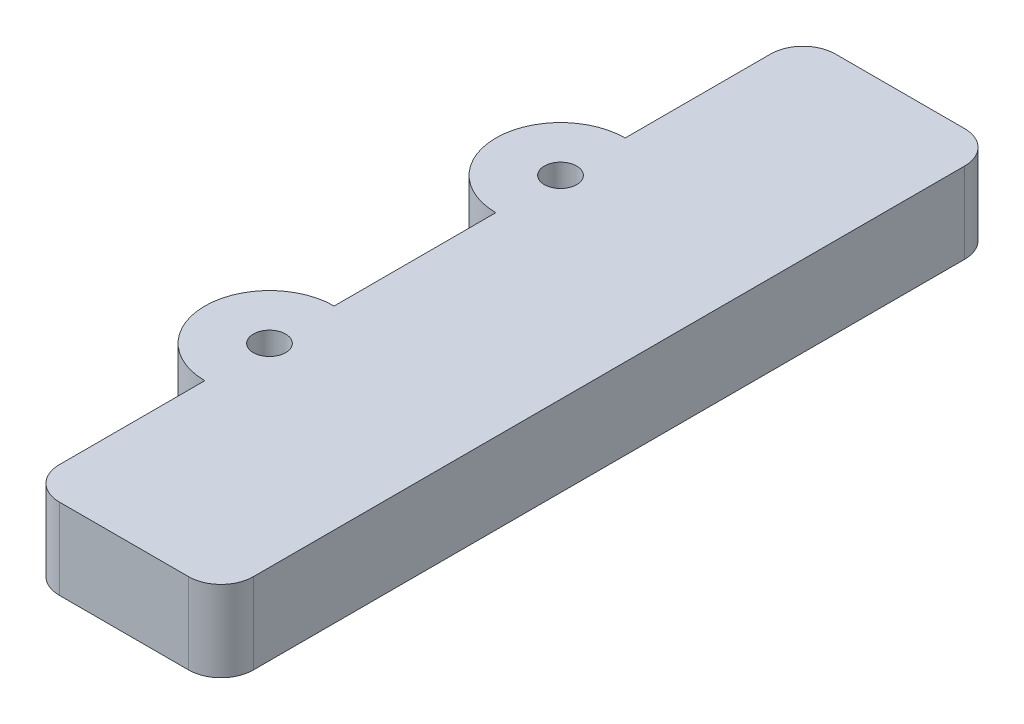
SolidWorks part; units mm, degrees
ref_plane "Front Plane" through (0, 0, 0) normal (0, 0, 1) x (1, 0, 0)
ref_plane "Top Plane" through (0, 0, 0) normal (0, 1, 0) x (1, 0, 0)
ref_plane "Right Plane" through (0, 0, 0) normal (1, 0, 0) x (0, 0, -1)
sketch "Sketch1" plane through (0, 0, 0) normal (0, 1, 0) x (1, 0, 0)
  line L0 (0, 0) -> (0, 11) construction
  line L1 (0, 0) -> (12, 0)
  line L3 (0, 48) -> (12, 48)
  line L4 (12, 0) -> (12, 48)
  line L5 (0, 0) -> (0, 11)
  line L6 (0, 37) -> (0, 48) construction
  line L7 (0, 37) -> (0, 48)
  line L8 (0, 19) -> (0, 29) construction
  line L9 (0, 19) -> (0, 29)
  arc A6 (0, 19) -> (0, 11) centre (0, 15) ccw
  arc A7 (0, 37) -> (0, 29) centre (0, 33) ccw
  circle A11 centre (0, 33) radius 1
  circle A12 centre (0, 15) radius 1
  dimension "D13" = 8
  dimension "D14" = 8
  dimension "D8" = 2
  dimension "D2" = 12
  dimension "D3" = 48
  dimension "D11" = 15
  dimension "D12" = 18
extrude "Boss-Extrude1" add sketch "Sketch1" along normal blind 5
fillet "Fillet2" radius 2 4 edges at (0, 2.5, 0) (12, 2.5, 0) (0, 2.5, -48) (12, 2.5, -48)
